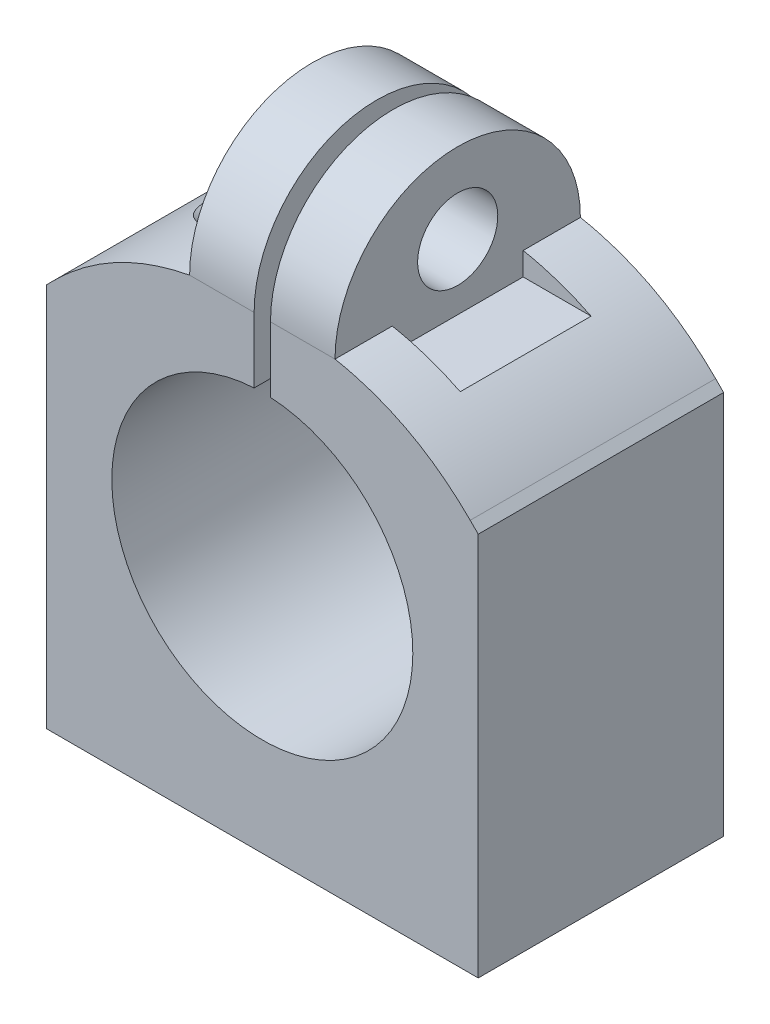
SolidWorks part; units mm, degrees
ref_plane "Front Plane" through (0, 0, 0) normal (0, 0, 1) x (1, 0, 0)
ref_plane "Top Plane" through (0, 0, 0) normal (0, 1, 0) x (1, 0, 0)
ref_plane "Right Plane" through (0, 0, 0) normal (1, 0, 0) x (0, 0, -1)
sketch "Sketch1" plane through (0, 0, 0) normal (0, 0, 1) x (1, 0, 0)
  line L0 (-16.764, 10.536) -> (-13.65, 13.65)
  line L1 (-16.764, -19.304) -> (16.764, -19.304)
  line L2 (-16.764, -19.304) -> (-16.764, 10.536)
  line L4 (16.764, -19.304) -> (16.764, 10.536)
  line L5 (16.764, 10.536) -> (13.65, 13.65)
  line L6 (-9.6016, 16.7467) -> (-0.635, 16.7467)
  line L8 (-0.635, 11.6667) -> (-0.635, 16.7467)
  line L10 (0.635, 11.6667) -> (0.635, 16.7467)
  line L11 (0.635, 16.7467) -> (9.6016, 16.7467)
  line L12 (0, 0) -> (11.684, 0) construction
  arc A0 (-0.635, 11.6667) -> (0.635, 11.6667) centre (0, 0) ccw
  arc A1 (13.65, 13.65) -> (9.6016, 16.7467) centre (0, 0) ccw
  arc A2 (-9.6016, 16.7467) -> (-13.65, 13.65) centre (0, 0) ccw
  dimension "D1" = 23.368
  dimension "D2" = 7.62
  dimension "D4" = 5.08
  dimension "D3" = 45
  dimension "D5" = 1.27
  dimension "D6" = 5.08
extrude "Boss-Extrude1" add sketch "Sketch1" along normal blind 19.05
sketch "Sketch2" plane through (0.635, 0, 0) normal (-1, 0, 0) x (0, 0, 1)
  line L0 (19.05, 16.7467) -> (0, 16.7467) construction
  line L7 (19.05, 16.7467) -> (0, 16.7467)
  arc A0 (19.05, 16.7467) -> (0, 16.7467) centre (9.525, 16.7467) ccw
  circle A1 centre (9.525, 20.0487) radius 3.1115
  dimension "D1" = 6.223
  dimension "D2" = 3.302
extrude "Boss-Extrude3" add sketch "Sketch2" against normal blind 5.0089
mirror "Mirror7" about plane through (0, 0, 0) normal (1, 0, 0) of "Boss-Extrude3"
sketch "Sketch3" plane through (-5.6439, 0, 0) normal (-1, 0, 0) x (0, 0, 1)
  circle A0 centre (9.525, 20.0487) radius 6.35
  circle A1 centre (9.525, 20.0487) radius 3.1115 construction
  point P2 (0, 0)
  dimension "D1" = 12.7
sketch "Sketch4" plane through (0, 0, 0) normal (0, 0, -1) x (-1, 0, 0)
  line L0 (-16.764, 10.536) -> (-13.65, 13.65) construction
  line L1 (-9.6016, 16.7467) -> (-5.6439, 16.7467) construction
  line L2 (-16.1412, 11.1587) -> (-16.1412, 17.7103)
  line L3 (-16.1412, 17.7103) -> (-5.6439, 16.7467)
  line L4 (0, 55) -> (0, -55) construction
  line L5 (16.1412, 17.7103) -> (5.6439, 16.7467)
  line L6 (16.1412, 11.1587) -> (16.1412, 17.7103)
  spline S0 degree 2 poles (-5.6439, 16.7467) (-11.7117, 15.5883) (-16.1412, 11.1587) knots 0 0 0 1 1 1
  spline S1 degree 2 poles (5.6439, 16.7467) (11.7117, 15.5883) (16.1412, 11.1587) knots 0 0 0 1 1 1
  dimension "D1" = 5.588
extrude "Cut-Extrude1" cut sketch "Sketch4" against normal through all
extrude "Cut-Extrude2" cut sketch "Sketch3" along normal through all contours A0
sketch "Sketch5" plane through (5.6439, 0, 0) normal (1, 0, 0) x (0, 0, -1)
  line L0 (-14.605, 25.1287) -> (-4.445, 14.9687) construction
  line L1 (-14.605, 25.1287) -> (-4.445, 25.1287)
  line L2 (-14.605, 25.1287) -> (-14.605, 14.9687)
  line L3 (-14.605, 14.9687) -> (-4.445, 14.9687)
  line L4 (-4.445, 25.1287) -> (-4.445, 14.9687)
  circle A1 centre (-9.525, 20.0487) radius 3.1115 construction
  point P4 (-9.525, 20.0487)
  dimension "D1" = 10.16
extrude "Cut-Extrude3" cut sketch "Sketch5" along normal through all
